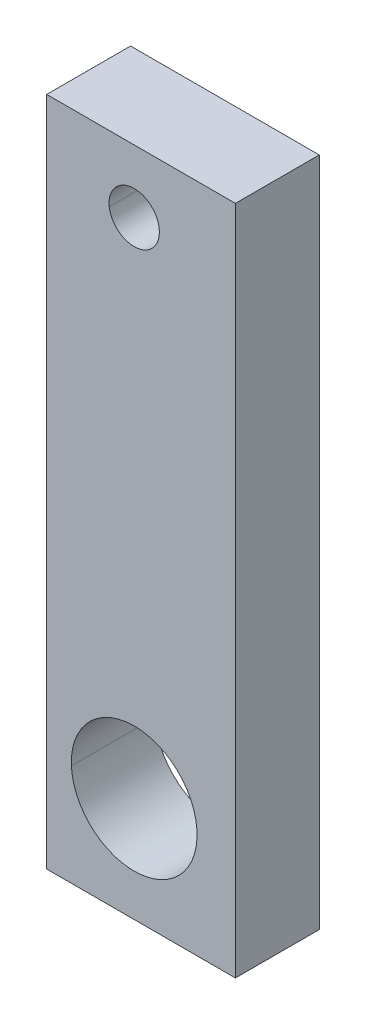
SolidWorks part; units mm, degrees
ref_plane "Płaszczyzna przednia" through (0, 0, 0) normal (0, 0, 1) x (1, 0, 0)
ref_plane "Płaszczyzna górna" through (0, 0, 0) normal (0, 1, 0) x (1, 0, 0)
ref_plane "Płaszczyzna prawa" through (0, 0, 0) normal (1, 0, 0) x (0, 0, -1)
sketch "Szkic1" plane through (0, 0, 0) normal (0, 0, 1) x (1, 0, 0)
  line L1 (0, 0) -> (45, 0)
  line L2 (0, 0) -> (0, -160)
  line L3 (0, -160) -> (45, -160)
  line L4 (45, 0) -> (45, -160)
  circle A0 centre (20.8621, -15) radius 6
  circle A1 centre (20.8621, -135) radius 15
  dimension "D3" = 12
  dimension "D4" = 30
  dimension "D1" = 45
  dimension "D2" = 160
  dimension "D5" = 25
  dimension "D6" = 120
extrude "Dodanie-wyciągnięcie1" add sketch "Szkic1" along normal blind 20
sketch "Szkic2" plane through (45, 0, 0) normal (1, 0, 0) x (0, 0, -1)
  line L0 (-20, -15.7418) -> (0, -15.7418)
  line L1 (-20, -160) -> (-20, 0) construction
  line L2 (0, -160) -> (0, 0) construction
  line L3 (0, -135.7418) -> (-20, -135.7418)
  dimension "D1" = 120
split line "Linia podziałowa1"
other "Grafika1" [suppressed]
other "Grafika (Zamknięta) -1"
sketch "Szkic4" [suppressed] plane through (0, 0, 0) normal (0, 0, 1) x (1, 0, 0)
  line L0 (16.8795, -33.0591) -> (15.4698, -108.7577)
  line L1 (26.8065, -32.7763) -> (26.0482, -108.5019)
  circle A0 centre (21.3224, -14.6452) radius 18.9423
  circle A1 centre (20.978, -134.7211) radius 27.173
  circle A2 centre (21.3224, -14.6452) radius 7.1837
  circle A3 centre (20.978, -134.7211) radius 15.1648
